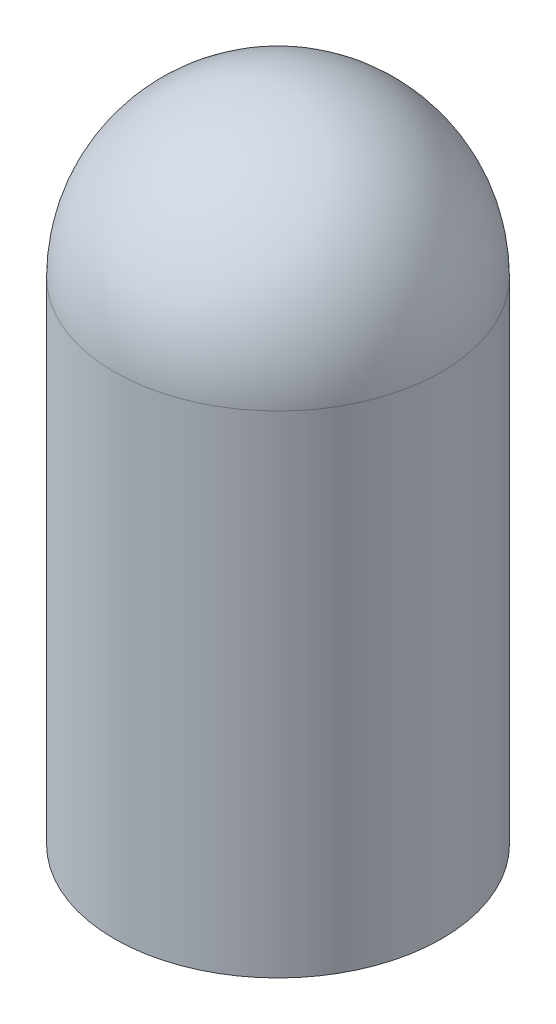
SolidWorks part; units mm, degrees
ref_plane "Front Plane" through (0, 0, 0) normal (0, 0, 1) x (1, 0, 0)
ref_plane "Top Plane" through (0, 0, 0) normal (0, 1, 0) x (1, 0, 0)
ref_plane "Right Plane" through (0, 0, 0) normal (1, 0, 0) x (0, 0, -1)
sketch "Sketch1" plane through (0, 0, 0) normal (0, 1, 0) x (1, 0, 0)
  circle A0 centre (0, 0) radius 5
  dimension "D1" = 10
extrude "Boss-Extrude1" add sketch "Sketch1" along normal blind 20
fillet "Fillet1" radius 5 1 edges at (0, 20, 5)
